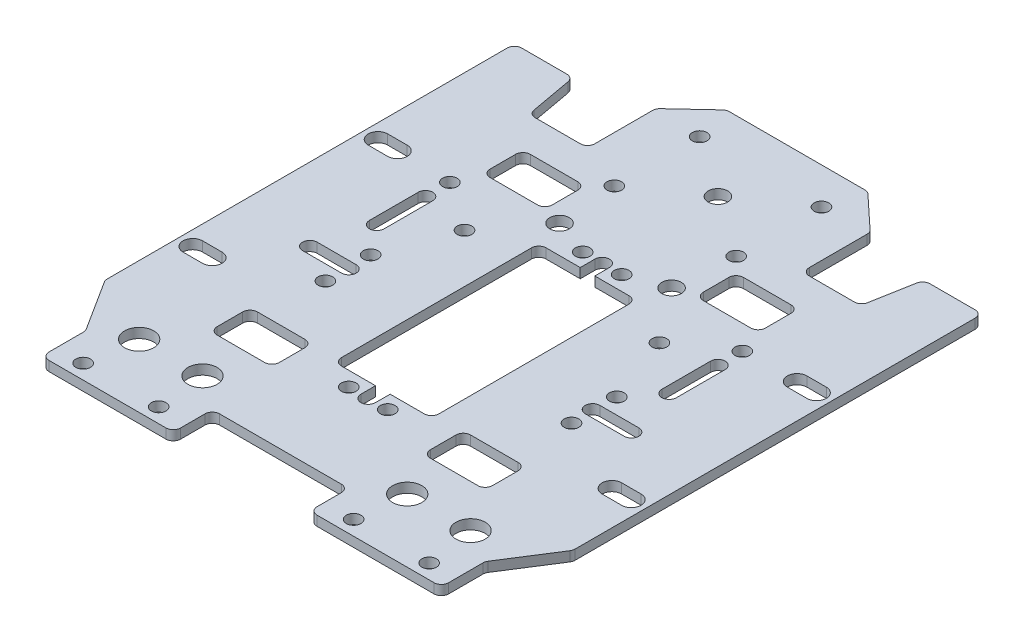
SolidWorks part; units mm, degrees
material "1060 Alloy"
ref_plane "Front Plane" through (0, 0, 0) normal (0, 0, 1) x (1, 0, 0)
ref_plane "Top Plane" through (0, 0, 0) normal (0, 1, 0) x (1, 0, 0)
ref_plane "Right Plane" through (0, 0, 0) normal (1, 0, 0) x (0, 0, -1)
sketch "Sketch1" plane through (0, 0, 0) normal (0, 1, 0) x (1, 0, 0)
  line L0 (48, 228) -> (48, 71.7384) construction
  line L2 (0, 20) -> (0, 104)
  line L4 (96, 20) -> (96, 104)
  line L5 (33.5, 114) -> (26, 107)
  line L6 (26, 107) -> (26, 93)
  line L7 (26, 93) -> (14, 93)
  line L8 (14, 93) -> (12, 104)
  line L9 (12, 104) -> (0, 104)
  line L10 (62.5, 114) -> (70, 107)
  line L11 (70, 107) -> (70, 93)
  line L12 (70, 93) -> (82, 93)
  line L13 (82, 93) -> (84, 104)
  line L14 (84, 104) -> (96, 104)
  line L15 (33.5, 114) -> (62.5, 114)
  line L16 (0, 20) -> (7, 9)
  line L17 (7, 9) -> (7, 0)
  line L18 (89, 9) -> (89, 0)
  line L19 (96, 20) -> (89, 9)
  line L20 (7, 0) -> (34, 0)
  line L21 (34, 0) -> (34, 8)
  line L22 (34, 8) -> (62, 8)
  line L23 (89, 0) -> (62, 0)
  line L24 (62, 0) -> (62, 8)
  line L25 (76.25, 21.75) -> (63.5, 21.75)
  line L26 (19.75, 30) -> (32.5, 30)
  line L27 (19.75, 30) -> (19.75, 21.75)
  line L28 (19.75, 21.75) -> (32.5, 21.75)
  line L29 (32.5, 30) -> (32.5, 21.75)
  line L30 (63.5, 30) -> (63.5, 21.75)
  line L31 (76.25, 30) -> (63.5, 30)
  line L32 (76.25, 30) -> (76.25, 21.75)
  line L33 (0, 53.875) -> (96, 53.875) construction
  line L34 (76.25, 77.75) -> (76.25, 86)
  line L35 (76.25, 77.75) -> (63.5, 77.75)
  line L36 (63.5, 77.75) -> (63.5, 86)
  line L37 (76.25, 86) -> (63.5, 86)
  line L38 (19.75, 86) -> (32.5, 86)
  line L39 (32.5, 77.75) -> (32.5, 86)
  line L40 (19.75, 77.75) -> (32.5, 77.75)
  line L41 (19.75, 77.75) -> (19.75, 86)
  line L42 (3, 75) -> (7, 75)
  line L43 (3, 71) -> (7, 71)
  line L44 (93, 75) -> (89, 75)
  line L45 (93, 71) -> (89, 71)
  line L46 (0, 54) -> (96, 54) construction
  line L47 (93, 37) -> (89, 37)
  line L48 (93, 33) -> (89, 33)
  line L49 (3, 33) -> (7, 33)
  line L50 (3, 37) -> (7, 37)
  line L51 (15, 48.5252) -> (23, 48.5252)
  line L52 (23, 45.5252) -> (15, 45.5252)
  line L53 (81, 48.5252) -> (73, 48.5252)
  line L54 (73, 45.5252) -> (81, 45.5252)
  line L55 (16.5, 67.75) -> (16.5, 57.75)
  line L56 (19.5, 67.75) -> (19.5, 57.75)
  line L57 (76.5, 67.75) -> (76.5, 57.75)
  line L58 (79.5, 67.75) -> (79.5, 57.75)
  line L59 (46.5, 29) -> (38, 29)
  line L60 (38, 29) -> (38, 71)
  line L61 (38, 71) -> (46.5, 71)
  line L62 (46.5, 29) -> (46.5, 26)
  line L63 (18.7278, 50) -> (57.2722, 50) construction
  line L64 (46.5, 71) -> (46.5, 74)
  line L65 (49.5, 29) -> (49.5, 26)
  line L66 (49.5, 29) -> (58, 29)
  line L67 (58, 29) -> (58, 71)
  line L68 (49.5, 71) -> (49.5, 74)
  line L69 (58, 71) -> (49.5, 71)
  line L70 (35.5, 106.5) -> (60.5, 89) construction
  circle A0 centre (12.5, 3) radius 1.5
  circle A1 centre (28, 3) radius 1.5
  circle A2 centre (68, 3) radius 1.5
  circle A3 centre (83.5, 3) radius 1.5
  circle A4 centre (14, 13) radius 3
  circle A5 centre (27, 13) radius 3
  circle A6 centre (69, 13) radius 3
  circle A7 centre (82, 13) radius 3
  arc A8 (3, 75) -> (3, 71) centre (3, 73) ccw
  arc A10 (7, 71) -> (7, 75) centre (7, 73) ccw
  arc A11 (89, 71) -> (89, 75) centre (89, 73) cw
  arc A12 (93, 75) -> (93, 71) centre (93, 73) cw
  arc A13 (93, 33) -> (93, 37) centre (93, 35) ccw
  arc A14 (89, 37) -> (89, 33) centre (89, 35) ccw
  arc A15 (7, 37) -> (7, 33) centre (7, 35) cw
  arc A16 (3, 33) -> (3, 37) centre (3, 35) cw
  circle A17 centre (22.75, 42.455) radius 1.5
  arc A18 (23, 45.5252) -> (23, 48.5252) centre (23, 47.0252) ccw
  arc A19 (15, 48.5252) -> (15, 45.5252) centre (15, 47.0252) ccw
  circle A20 centre (22.75, 51.7511) radius 1.5
  circle A21 centre (73.25, 42.455) radius 1.5
  arc A22 (73, 45.5252) -> (73, 48.5252) centre (73, 47.0252) cw
  arc A23 (81, 48.5252) -> (81, 45.5252) centre (81, 47.0252) cw
  circle A24 centre (73.25, 51.7511) radius 1.5
  circle A25 centre (18, 72.75) radius 1.5
  arc A26 (19.5, 67.75) -> (16.5, 67.75) centre (18, 67.75) ccw
  arc A27 (16.5, 57.75) -> (19.5, 57.75) centre (18, 57.75) ccw
  circle A28 centre (28, 65.75) radius 1.5
  circle A29 centre (68, 65.75) radius 1.5
  circle A30 centre (78, 72.75) radius 1.5
  arc A31 (79.5, 57.75) -> (76.5, 57.75) centre (78, 57.75) cw
  arc A32 (76.5, 67.75) -> (79.5, 67.75) centre (78, 67.75) cw
  circle A33 centre (36.5, 76.75) radius 2
  circle A34 centre (59.5, 76.75) radius 2
  circle A35 centre (35.5, 89) radius 1.5
  circle A36 centre (35.5, 106.5) radius 1.5
  circle A37 centre (60.5, 89) radius 1.5
  circle A38 centre (60.5, 106.5) radius 1.5
  arc A39 (46.5, 26) -> (49.5, 26) centre (48, 26) ccw
  arc A40 (46.5, 74) -> (49.5, 74) centre (48, 74) cw
  circle A41 centre (44, 26) radius 1.5
  circle A42 centre (52, 26) radius 1.5
  circle A43 centre (52, 74) radius 1.5
  circle A44 centre (44, 74) radius 1.5
  circle A45 centre (48, 97.75) radius 2
  point P8 (48, 149.8692)
  point P28 (48, 8)
  point P150 (38, 50)
  dimension "D13" = 3
  dimension "D14" = 3
  dimension "D15" = 5.5
  dimension "D16" = 6
  dimension "D17" = 3
  dimension "D18" = 6
  dimension "D19" = 13
  dimension "D20" = 14
  dimension "D21" = 13
  dimension "D27" = 4
  dimension "D28" = 4
  dimension "D29" = 4
  dimension "D30" = 31
  dimension "D32" = 3
  dimension "D34" = 3
  dimension "D35" = 3
  dimension "D36" = 22.75
  dimension "D37" = 3
  dimension "D39" = 15
  dimension "D40" = 3
  dimension "D41" = 11
  dimension "D42" = 5
  dimension "D43" = 5
  dimension "D44" = 10
  dimension "D45" = 3
  dimension "D46" = 10
  dimension "D47" = 7
  dimension "D48" = 4
  dimension "D49" = 4
  dimension "D50" = 1
  dimension "D51" = 3
  dimension "D52" = 3
  dimension "D53" = 3
  dimension "D54" = 17.5
  dimension "D55" = 21
  dimension "D60" = 3
  dimension "D61" = 3
  dimension "D58" = 3
  dimension "D62" = 4
  dimension "D63" = 4
  dimension "D1" = 10
  dimension "D2" = 96
  dimension "D3" = 12
  dimension "D4" = 21
  dimension "D5" = 7
  dimension "D6" = 7.5
  dimension "D7" = 12
  dimension "D8" = 2
  dimension "D9" = 27
  dimension "D10" = 7
  dimension "D11" = 9
  dimension "D12" = 8
  dimension "D22" = 8.25
  dimension "D23" = 12.75
  dimension "D24" = 21.75
  dimension "D25" = 19.75
  dimension "D26" = 23.875
  dimension "D31" = 114
  dimension "D33" = 17
  dimension "D38" = 8
  dimension "D56" = 42
  dimension "D57" = 38
  dimension "D59" = 1.5
extrude "Boss-Extrude1" add sketch "Sketch1" along normal blind 2
fillet "Fillet1" radius 1.5 42 edges at (38, 1, -29) (58, 1, -71) (63.5, 1, -30) (63.5, 1, -86) (32.5, 1, -86) (32.5, 1, -30) (76.25, 1, -30) (76.25, 1, -86) (19.75, 1, -77.75) (63.5, 1, -77.75) (63.5, 1, -21.75) (19.75, 1, -21.75) (32.5, 1, -21.75) (32.5, 1, -77.75) (76.25, 1, -77.75) (58, 1, -29) (76.25, 1, -21.75) (0, 1, -104) (12, 1, -104) (14, 1, -93) (26, 1, -93) (26, 1, -107) (33.5, 1, -114) (62.5, 1, -114) (70, 1, -107) (70, 1, -93) (82, 1, -93) (84, 1, -104) (96, 1, -104) (96, 1, -20) (89, 1, -9) (89, 1, 0) (62, 1, -8) (62, 1, 0) (19.75, 1, -86) (38, 1, -71) (19.75, 1, -30) (34, 1, -8) (34, 1, 0) (0, 1, -20) (7, 1, -9) (7, 1, 0)
